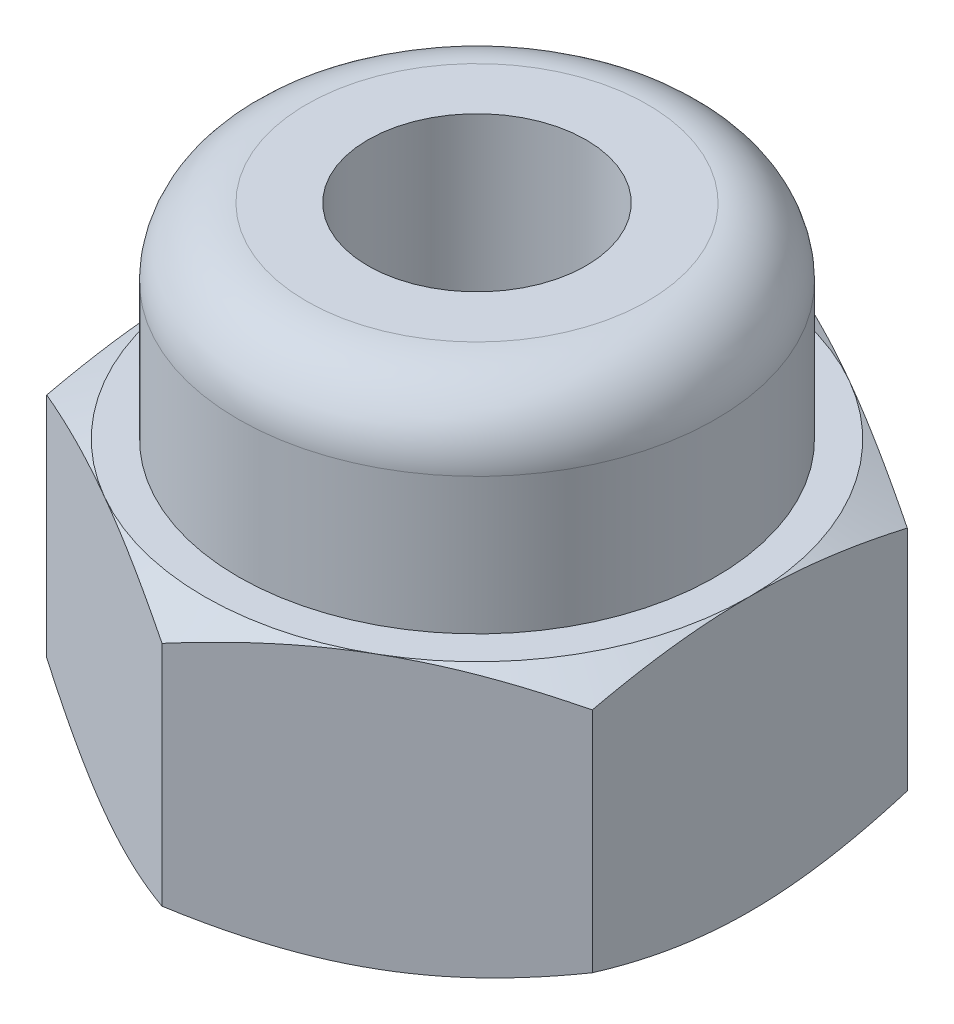
SolidWorks part; units mm, degrees
material "AISI 321 退火不锈钢 (SS)"
ref_plane "前视基准面" through (0, 0, 0) normal (0, 0, 1) x (1, 0, 0)
ref_plane "上视基准面" through (0, 0, 0) normal (0, 1, 0) x (1, 0, 0)
ref_plane "右视基准面" through (0, 0, 0) normal (1, 0, 0) x (0, 0, -1)
other "Configuration Table"
sketch "草图1" plane through (0, 0, 0) normal (0, 1, 0) x (1, 0, 0)
  line L1 (2, 1.1547) -> (0, 2.3094)
  line L2 (0, 2.3094) -> (-2, 1.1547)
  line L3 (-2, 1.1547) -> (-2, -1.1547)
  line L4 (-2, -1.1547) -> (0, -2.3094)
  line L5 (0, -2.3094) -> (2, -1.1547)
  line L6 (2, -1.1547) -> (2, 1.1547)
  circle A0 centre (0, 0) radius 2 construction
  dimension "D1" = 4
extrude "凸台-拉伸1" add sketch "草图1" along normal blind 2
sketch "草图2" plane through (0, 2, 0) normal (0, 1, 0) x (1, 0, 0)
  circle A0 centre (0, 0) radius 1.75
  dimension "D1" = 3.5
extrude "凸台-拉伸2" add sketch "草图2" along normal blind 1.5
fillet "圆角1" radius 0.5 1 edges at (0, 3.5, 1.75)
sketch "草图3" plane through (0, 0, 0) normal (0, -1, 0) x (1, 0, 0)
  circle A0 centre (0, 0) radius 0.8
  dimension "D1" = 1.6
extrude "切除-拉伸1" cut sketch "草图3" against normal blind 3.5
cosmetic thread "装饰螺纹线1" parameters "D2"=3
sketch "草图4" plane through (0, 0, 0) normal (0, 0, 1) x (1, 0, 0)
  line L0 (3.4542, 0) -> (3.4542, 0.8841)
  line L1 (0, 0) -> (2, 0) construction
  line L2 (2, 2) -> (2, 0) construction
  line L3 (3.4542, 0.8841) -> (2, 0)
  line L4 (2, 0) -> (3.4542, 0)
  line L5 (0, 0) -> (0, 0.8841) construction
  line L6 (0, 2) -> (0, 0) construction
  line L7 (2, 2) -> (3.4542, 2)
  line L8 (3.4542, 2) -> (3.4542, 1.3288)
  line L9 (3.4542, 1.3288) -> (2, 2)
revolve "切除-旋转1" cut sketch "草图4" angle 360 about L5
